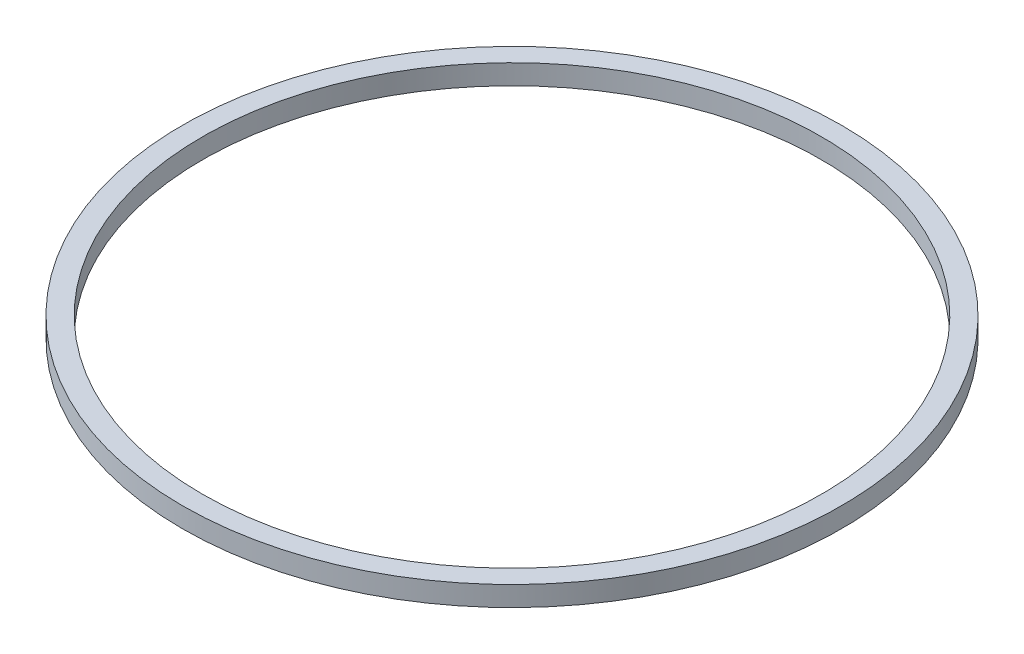
SolidWorks part; units mm, degrees
material "Резина"
ref_plane "Спереди" through (0, 0, 0) normal (0, 0, 1) x (1, 0, 0)
ref_plane "Сверху" through (0, 0, 0) normal (0, 1, 0) x (1, 0, 0)
ref_plane "Справа" through (0, 0, 0) normal (1, 0, 0) x (0, 0, -1)
sketch "Эскиз1" plane through (0, 0, 0) normal (0, 1, 0) x (1, 0, 0)
  circle A0 centre (0, 0) radius 31
  circle A1 centre (0, 0) radius 33
  dimension "D1" = 2
  dimension "D2" = 62
extrude "Бобышка-Вытянуть1" add sketch "Эскиз1" along normal blind 2
